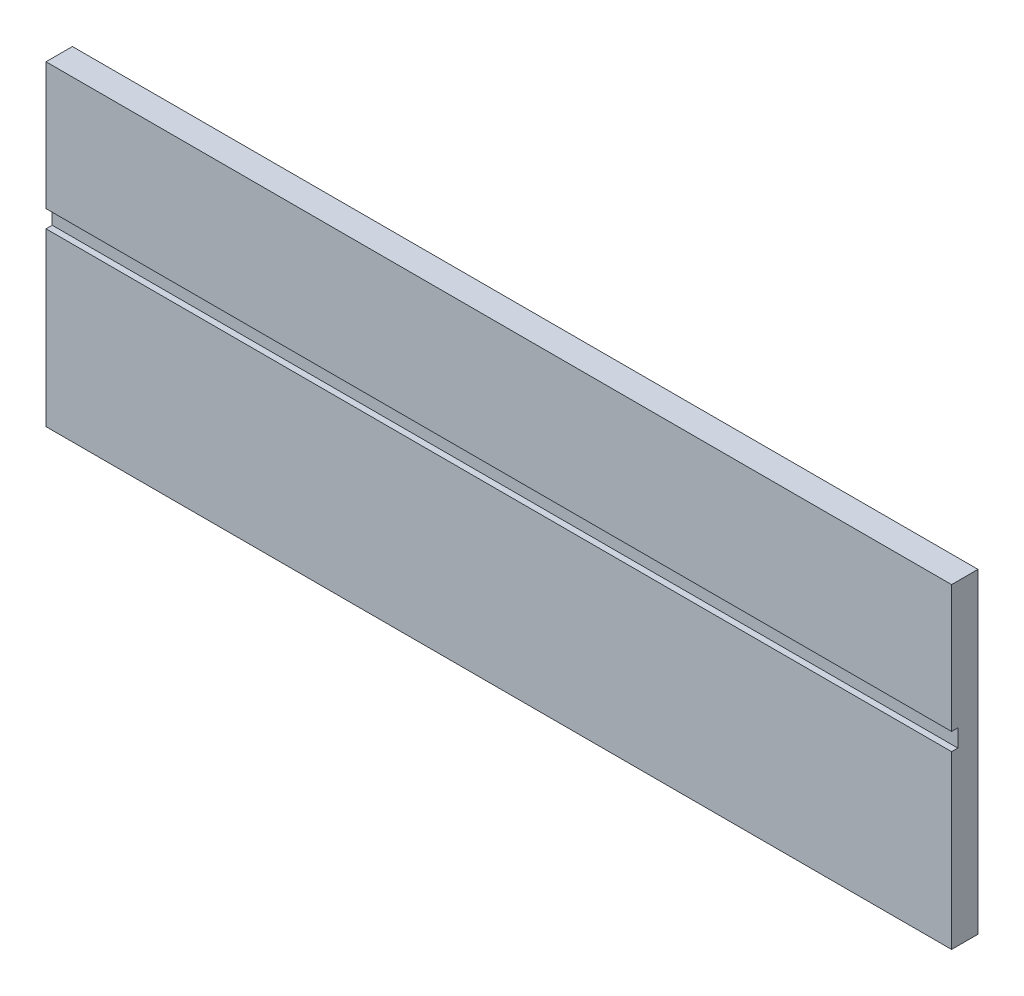
SolidWorks part; units mm, degrees
material "Pine"
ref_plane "Front Plane" through (0, 0, 0) normal (0, 0, 1) x (1, 0, 0)
ref_plane "Top Plane" through (0, 0, 0) normal (0, 1, 0) x (1, 0, 0)
ref_plane "Right Plane" through (0, 0, 0) normal (1, 0, 0) x (0, 0, -1)
sketch "Sketch1" plane through (0, 0, 0) normal (0, 0, 1) x (1, 0, 0)
  line L0 (-163.9887, -5335.905) -> (-163.9887, -5432.425)
  line L1 (-102.87, -5350.891) -> (-33.02, -5350.891)
  line L2 (-111.8235, -5341.9375) -> (-111.8235, -5334)
  line L3 (-24.0665, -5341.9375) -> (-24.0665, -5334)
  line L4 (-298.9262, -5332.73) -> (-167.1637, -5332.73)
  line L5 (-167.1637, -5435.6) -> (-298.9262, -5435.6)
  line L6 (-302.1012, -5432.425) -> (-302.1012, -5335.905)
  line L7 (-107.6325, -5329.809) -> (-28.2575, -5329.809)
  line L8 (174.9425, -5308.6) -> (174.9425, -5581.65)
  line L9 (449.2625, -5413.1661) -> (449.2625, -5421.9659)
  line L10 (595.3125, -5421.9659) -> (595.3125, -5413.1661)
  line L11 (839.47, -5509.5521) -> (839.47, -5307.6729)
  line L12 (839.47, -5307.6729) -> (863.6, -5307.6729)
  line L13 (839.47, -5509.5521) -> (863.6, -5509.5521)
  line L14 (863.6, -5509.5521) -> (863.6, -5307.6729)
  line L15 (-354.2665, -5341.9375) -> (-354.2665, -5334)
  line L16 (-100.8856, -5889.625) -> (-50.0856, -5889.625)
  line L17 (-104.0606, -5969) -> (-104.0606, -5892.8)
  line L18 (-46.9106, -5892.8) -> (-46.9106, -5969)
  line L19 (-50.0856, -5972.175) -> (-100.8856, -5972.175)
  line L20 (-100.8856, -5848.35) -> (-50.0856, -5848.35)
  line L21 (857.25, -5502.275) -> (157.1625, -5575.3)
  line L22 (857.25, -5314.95) -> (857.25, -5502.275)
  line L23 (157.1625, -5314.95) -> (157.1625, -5575.3)
  line L24 (857.25, -5314.95) -> (157.1625, -5314.95)
  line L25 (150.8125, -5308.6) -> (174.9425, -5308.6)
  line L26 (174.9425, -5581.65) -> (150.8125, -5581.65)
  line L27 (137.16, -5314.95) -> (137.16, -5502.275)
  line L28 (150.8125, -5581.65) -> (150.8125, -5308.6)
  line L29 (590.8224, -5408.676) -> (453.7526, -5408.676)
  line L30 (453.7526, -5426.456) -> (590.8224, -5426.456)
  line L31 (137.16, -6013.45) -> (137.16, -5867.4)
  line L32 (150.8125, -5746.75) -> (150.8125, -6019.8)
  line L33 (143.51, -5639.9938) -> (143.51, -5654.294)
  line L34 (590.8224, -5919.724) -> (453.7526, -5919.724)
  line L35 (453.7526, -5901.944) -> (590.8224, -5901.944)
  line L36 (449.2625, -5915.2339) -> (449.2625, -5906.4341)
  line L37 (174.9425, -6019.8) -> (174.9425, -5746.75)
  line L38 (595.3125, -5906.4341) -> (595.3125, -5915.2339)
  line L39 (839.47, -5818.8479) -> (839.47, -6020.7271)
  line L40 (839.47, -5818.8479) -> (863.6, -5818.8479)
  line L41 (863.6, -5818.8479) -> (863.6, -6020.7271)
  line L42 (839.47, -6020.7271) -> (863.6, -6020.7271)
  line L43 (-155.8782, -5867.4) -> (-603.25, -5867.4)
  line L44 (-433.07, -5350.891) -> (-363.22, -5350.891)
  line L45 (-437.8325, -5329.809) -> (-358.4575, -5329.809)
  line L46 (889, -6045.2) -> (-635, -6045.2)
  line L47 (-635, -5283.2) -> (889, -5283.2)
  line L48 (-635, -6045.2) -> (-635, -5283.2)
  line L49 (889, -5283.2) -> (889, -6045.2)
  line L50 (137.16, -5502.275) -> (-603.25, -5502.275)
  line L51 (-603.25, -5314.95) -> (137.16, -5314.95)
  line L52 (143.51, -5654.294) -> (-609.6, -5654.294)
  line L53 (-609.6, -5639.9938) -> (143.51, -5639.9938)
  line L54 (137.16, -5536.0062) -> (-603.25, -5536.0062)
  line L55 (-603.25, -5794.375) -> (137.16, -5794.375)
  line L56 (-603.25, -6013.45) -> (137.16, -6013.45)
  line L57 (-603.25, -5536.0062) -> (-603.25, -5794.375)
  line L58 (137.16, -5794.375) -> (137.16, -5536.0062)
  line L59 (-609.6, -5654.294) -> (-609.6, -5639.9938)
  line L60 (-603.25, -5867.4) -> (-603.25, -6013.45)
  line L61 (-603.25, -5314.95) -> (-603.25, -5502.275)
  line L62 (-442.0235, -5341.9375) -> (-442.0235, -5334)
  line L63 (857.25, -5826.125) -> (157.1625, -5753.1)
  line L64 (857.25, -6013.45) -> (857.25, -5826.125)
  line L65 (157.1625, -6013.45) -> (157.1625, -5753.1)
  line L66 (857.25, -6013.45) -> (157.1625, -6013.45)
  line L67 (174.9425, -5746.75) -> (150.8125, -5746.75)
  line L68 (150.8125, -6019.8) -> (174.9425, -6019.8)
  line L69 (137.16, -5867.4) -> (4.907, -5867.4)
  circle A0 centre (-36.195, -5484.0124) radius 1.5875
  arc A1 (-298.9262, -5332.73) -> (-302.1012, -5335.905) centre (-298.9262, -5335.905) ccw
  arc A2 (-302.1012, -5432.425) -> (-298.9262, -5435.6) centre (-298.9262, -5432.425) ccw
  arc A3 (-163.9887, -5335.905) -> (-167.1637, -5332.73) centre (-167.1637, -5335.905) ccw
  arc A4 (-167.1637, -5435.6) -> (-163.9887, -5432.425) centre (-167.1637, -5432.425) ccw
  arc A5 (-111.8235, -5341.9375) -> (-102.87, -5350.891) centre (-102.87, -5341.9375) ccw
  arc A6 (-107.6325, -5329.809) -> (-111.8235, -5334) centre (-107.6325, -5334) ccw
  circle A7 centre (166.0525, -5444.6613) radius 1.5875
  circle A8 centre (166.0525, -5358.1871) radius 1.5875
  circle A9 centre (471.4875, -5417.566) radius 1.5875
  arc A10 (453.7526, -5408.676) -> (449.2625, -5413.1661) centre (451.5076, -5410.9211) ccw
  arc A11 (449.2625, -5421.9659) -> (453.7526, -5426.456) centre (451.5076, -5424.2109) ccw
  circle A12 centre (522.2875, -5417.566) radius 1.5875
  circle A13 centre (573.0875, -5417.566) radius 1.5875
  arc A14 (590.8224, -5426.456) -> (595.3125, -5421.9659) centre (593.0674, -5424.2109) ccw
  arc A15 (595.3125, -5413.1661) -> (590.8224, -5408.676) centre (593.0674, -5410.9211) ccw
  circle A16 centre (848.36, -5471.8269) radius 1.5875
  circle A17 centre (848.36, -5409.0762) radius 1.5875
  circle A18 centre (848.36, -5346.3254) radius 1.5875
  arc A19 (-363.22, -5350.891) -> (-354.2665, -5341.9375) centre (-363.22, -5341.9375) ccw
  arc A20 (-354.2665, -5334) -> (-358.4575, -5329.809) centre (-358.4575, -5334) ccw
  arc A21 (-24.0665, -5334) -> (-28.2575, -5329.809) centre (-28.2575, -5334) ccw
  arc A22 (-33.02, -5350.891) -> (-24.0665, -5341.9375) centre (-33.02, -5341.9375) ccw
  circle A23 centre (-86.995, -5484.0124) radius 1.5875
  circle A24 centre (-333.4544, -5894.07) radius 2.54
  circle A25 centre (-333.4544, -5994.4) radius 2.54
  arc A26 (-104.0606, -5969) -> (-100.8856, -5972.175) centre (-100.8856, -5969) ccw
  arc A27 (-50.0856, -5972.175) -> (-46.9106, -5969) centre (-50.0856, -5969) ccw
  arc A28 (-100.8856, -5848.35) -> (-128.3819, -5857.875) centre (-100.8856, -5892.8) ccw
  arc A29 (-155.8782, -5867.4) -> (-128.3819, -5857.875) centre (-155.8782, -5822.95) ccw
  arc A30 (-22.5893, -5857.875) -> (-50.0856, -5848.35) centre (-50.0856, -5892.8) ccw
  circle A31 centre (-132.6356, -5894.07) radius 2.54
  circle A32 centre (-132.6356, -5994.4) radius 2.54
  arc A33 (-46.9106, -5892.8) -> (-50.0856, -5889.625) centre (-50.0856, -5892.8) ccw
  arc A34 (-100.8856, -5889.625) -> (-104.0606, -5892.8) centre (-100.8856, -5892.8) ccw
  arc A35 (-22.5893, -5857.875) -> (4.907, -5867.4) centre (4.907, -5822.95) ccw
  circle A36 centre (166.0525, -5531.1356) radius 1.5875
  arc A37 (449.2625, -5915.2339) -> (453.7526, -5919.724) centre (451.5076, -5917.4789) ccw
  arc A38 (453.7526, -5901.944) -> (449.2625, -5906.4341) centre (451.5076, -5904.1891) ccw
  circle A39 centre (166.0525, -5797.2644) radius 1.5875
  circle A40 centre (166.0525, -5883.7387) radius 1.5875
  circle A41 centre (166.0525, -5970.2129) radius 1.5875
  circle A42 centre (471.4875, -5910.834) radius 1.5875
  circle A43 centre (522.2875, -5910.834) radius 1.5875
  circle A44 centre (573.0875, -5910.834) radius 1.5875
  arc A45 (595.3125, -5906.4341) -> (590.8224, -5901.944) centre (593.0674, -5904.1891) ccw
  arc A46 (590.8224, -5919.724) -> (595.3125, -5915.2339) centre (593.0674, -5917.4789) ccw
  circle A47 centre (848.36, -5919.3238) radius 1.5875
  circle A48 centre (848.36, -5982.0746) radius 1.5875
  circle A49 centre (848.36, -5856.5731) radius 1.5875
  arc A50 (-437.8325, -5329.809) -> (-442.0235, -5334) centre (-437.8325, -5334) ccw
  circle A51 centre (-429.895, -5484.0124) radius 1.5875
  arc A52 (-442.0235, -5341.9375) -> (-433.07, -5350.891) centre (-433.07, -5341.9375) ccw
  circle A53 centre (-379.095, -5484.0124) radius 1.5875
sketch "Sketch2" plane through (0, 0, 0) normal (0, 0, 1) x (1, 0, 0)
  line L0 (137.16, -5794.375) -> (137.16, -5536.0062)
  line L1 (137.16, -5536.0062) -> (-603.25, -5536.0062)
  line L2 (-603.25, -5536.0062) -> (-603.25, -5794.375)
  line L3 (-603.25, -5794.375) -> (137.16, -5794.375)
extrude "Extrude1" add sketch "Sketch2" against normal blind 21.59
sketch "Sketch3" plane through (0, 0, 0) normal (0, 0, 1) x (1, 0, 0)
  line L0 (-603.25, -5639.9938) -> (137.16, -5639.9938)
  line L1 (-609.6, -5639.9938) -> (143.51, -5639.9938) construction
  line L2 (-603.25, -5536.0062) -> (-603.25, -5794.375) construction
  line L3 (137.16, -5794.375) -> (137.16, -5536.0062) construction
  line L4 (137.16, -5639.9938) -> (137.16, -5654.294)
  line L5 (143.51, -5654.294) -> (-609.6, -5654.294) construction
  line L6 (137.16, -5654.294) -> (-603.25, -5654.294)
  line L7 (-603.25, -5654.294) -> (-603.25, -5639.9938)
extrude "Cut-Extrude1" cut sketch "Sketch3" against normal blind 5.08
